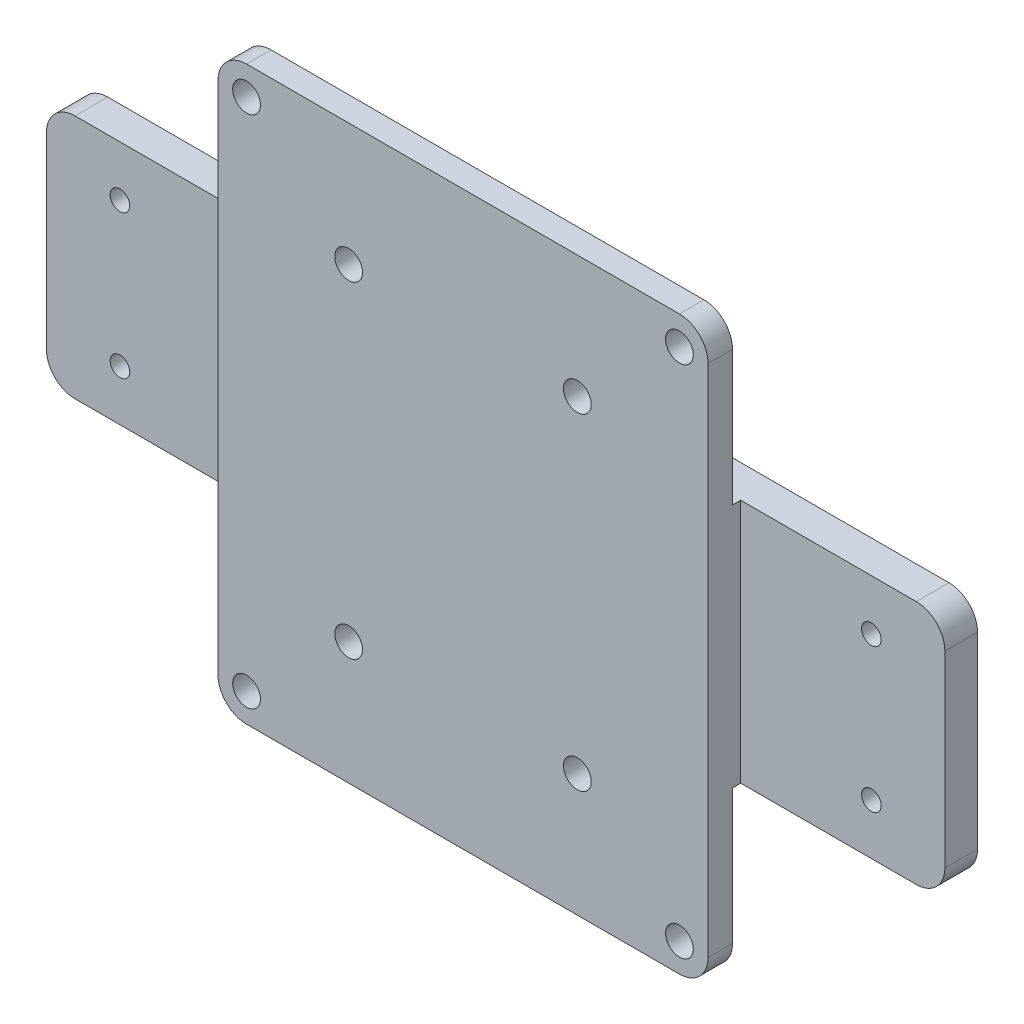
SolidWorks part; units mm, degrees
ref_plane "Front Plane" through (0, 0, 0) normal (1, 0, 0) x (0, 1, 0)
ref_plane "Top Plane" through (0, 0, 0) normal (0, 0, 1) x (0, 1, 0)
ref_plane "Right Plane" through (0, 0, 0) normal (0, 1, 0) x (-1, 0, 0)
sketch "Sketch2" plane through (0, 0, 0) normal (0, 0, 1) x (0, 1, 0)
  line L1 (-31.5, -30) -> (31.5, -30)
  line L2 (-35, -26.5) -> (-35, 26.5)
  line L3 (-31.5, 30) -> (31.5, 30)
  line L4 (35, -26.5) -> (35, 26.5)
  line L5 (-35, -30) -> (35, 30) construction
  line L6 (-35, 30) -> (35, -30) construction
  line L12 (35, -17.5) -> (35, 17.5)
  line L13 (0, 30) -> (-27, 30)
  line L17 (0, -30) -> (-27, -30)
  line L30 (-35, -17.5) -> (-35, 17.5)
  line L31 (35, -17.5) -> (-35, 17.5) construction
  line L32 (35, 17.5) -> (-35, -17.5) construction
  line L37 (-20, -14) -> (20, 14) construction
  line L38 (-20, 14) -> (20, -14) construction
  arc A4 (-35, 26.5) -> (-31.5, 30) centre (-31.5, 26.5) cw
  arc A5 (31.5, 30) -> (35, 26.5) centre (31.5, 26.5) cw
  arc A6 (-31.5, -30) -> (-35, -26.5) centre (-31.5, -26.5) cw
  arc A7 (31.5, -30) -> (35, -26.5) centre (31.5, -26.5) ccw
  circle A8 centre (-31.5, 26.5) radius 1.7
  circle A9 centre (31.5, 26.5) radius 1.7
  circle A10 centre (-31.5, -26.5) radius 1.7
  circle A11 centre (31.5, -26.5) radius 1.7
  circle A12 centre (-20, 14) radius 1.7
  circle A13 centre (20, 14) radius 1.7
  circle A14 centre (-20, -14) radius 1.7
  circle A15 centre (20, -14) radius 1.7
  point P0 (0, 0)
  point P6 (35, 0)
  point P27 (0, 0)
  point P32 (0, 0)
  dimension "D3" = 3.5
  dimension "D4" = 3.5
  dimension "D5" = 3.5
  dimension "D6" = 3.5
  dimension "D7" = 35
  dimension "D1" = 60
  dimension "D2" = 70
  dimension "D8" = 28
  dimension "D9" = 40
extrude "Boss-Extrude2" add sketch "Sketch2" along normal blind 3 contours L1 A7 L4 A5 L3 A4 L2 A6 A15 A14 A13 A12 A11 A10 A9 A8
sketch "Sketch3" plane through (30, 0, 0) normal (1, 0, 0) x (0, 1, 0)
  line L0 (-15, 0) -> (15, 0)
  line L2 (-15, 0) -> (-15, -5)
  line L3 (-15, -5) -> (15, -5)
  line L4 (15, 0) -> (15, -5)
  line L5 (0, 0) -> (15, -5) construction
  line L6 (-15, -5) -> (0, 0) construction
  point P0 (0, 0)
  dimension "D1" = 30
extrude "Boss-Extrude3" add sketch "Sketch3" against normal blind 5
sketch "Sketch4" plane through (-30, 0, 0) normal (-1, 0, 0) x (0, -1, 0)
  line L1 (-15, 0) -> (15, 0)
  line L2 (-15, 0) -> (-15, -5)
  line L3 (-15, -5) -> (15, -5)
  line L4 (15, 0) -> (15, -5)
extrude "Boss-Extrude4" add sketch "Sketch4" against normal blind 5
sketch "Sketch5" plane through (-30, 0, 0) normal (-1, 0, 0) x (0, -1, 0)
  line L0 (15, -5) -> (15, 0) construction
  line L1 (-15, -5) -> (15, -5)
  line L2 (-15, -5) -> (-15, -1)
  line L3 (-15, -1) -> (15, -1)
  line L4 (15, -5) -> (15, -1)
  dimension "D1" = 4
  dimension "D2" = 30
extrude "Boss-Extrude5" add sketch "Sketch5" along normal blind 25
sketch "Sketch6" plane through (30, 0, 0) normal (1, 0, 0) x (0, 1, 0)
  line L0 (15, -5) -> (15, 0) construction
  line L1 (-15, -5) -> (15, -5)
  line L2 (-15, -5) -> (-15, -1)
  line L3 (-15, -1) -> (15, -1)
  line L4 (15, -5) -> (15, -1)
  dimension "D1" = 4
extrude "Boss-Extrude8" add sketch "Sketch6" along normal blind 25
sketch "Sketch8" plane through (0, 0, -1) normal (0, 0, 1) x (0, -1, 0)
  line L0 (0, -55) -> (0, -46) construction
  line L1 (15, -55) -> (-15, -55) construction
  line L3 (0, -46) -> (-8.8, -46) construction
  line L5 (0, -46) -> (8.8, -46) construction
  line L7 (0, 55) -> (0, 46) construction
  line L8 (-15, 55) -> (15, 55) construction
  line L10 (0, 46) -> (-8.8, 46) construction
  line L11 (0, 46) -> (8.8, 46) construction
  circle A0 centre (-8.8, -46) radius 1.2
  circle A1 centre (8.8, -46) radius 1.2
  circle A2 centre (-8.8, 46) radius 1.2
  circle A3 centre (8.8, 46) radius 1.2
  dimension "D1" = 9
  dimension "D2" = 8.8
  dimension "D3" = 8.8
  dimension "D4" = 9
  dimension "D5" = 8.8
  dimension "D6" = 8.8
extrude "Cut-Extrude1" cut sketch "Sketch8" against normal blind 25
fillet "Fillet5" radius 3.5 1 edges at (-55, -15, -3)
fillet "Fillet6" radius 3.5 1 edges at (-55, 15, -3)
fillet "Fillet7" radius 3.5 1 edges at (55, 15, -3)
fillet "Fillet8" radius 3.5 1 edges at (55, -15, -3)
